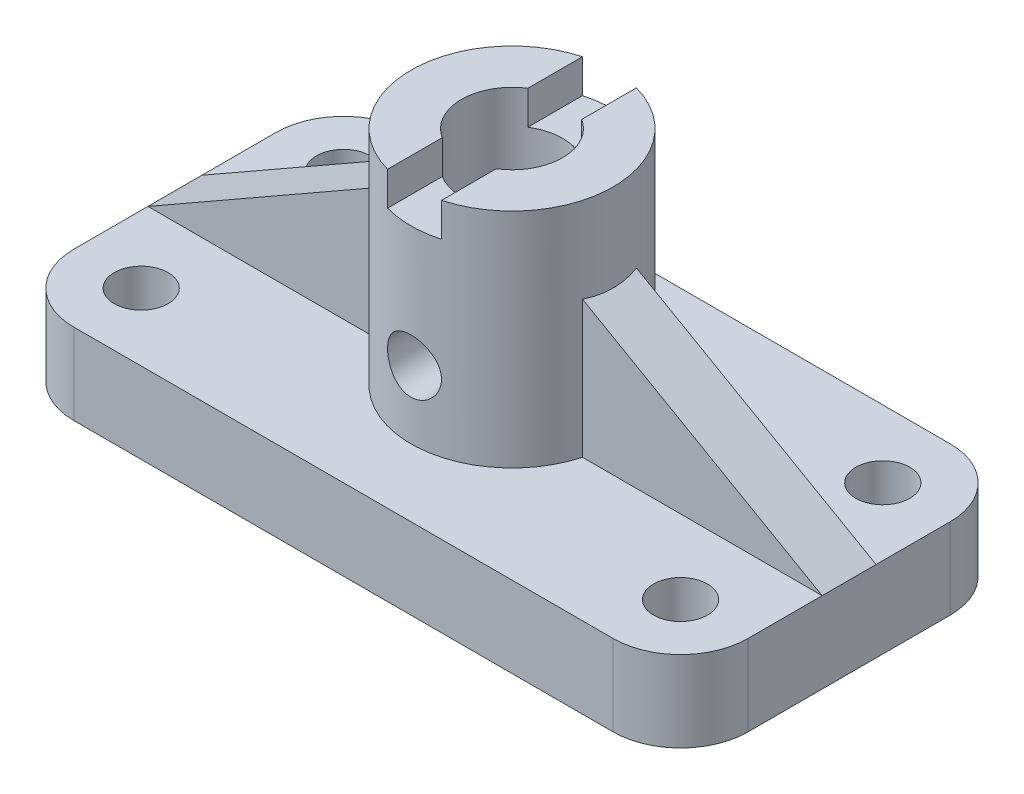
SolidWorks part; units mm, degrees
ref_plane "前视基准面" through (0, 0, 0) normal (0, 0, 1) x (1, 0, 0)
ref_plane "上视基准面" through (0, 0, 0) normal (0, 1, 0) x (1, 0, 0)
ref_plane "右视基准面" through (0, 0, 0) normal (1, 0, 0) x (0, 0, -1)
other "Configuration Table"
sketch "草图1" plane through (0, 0, 0) normal (0, 1, 0) x (1, 0, 0)
  line L1 (-40, -25) -> (40, -25)
  line L2 (-50, -15) -> (-50, 15)
  line L3 (-40, 25) -> (40, 25)
  line L4 (50, -15) -> (50, 15)
  line L5 (-50, -25) -> (50, 25) construction
  line L6 (-50, 25) -> (50, -25) construction
  line L7 (-40, -15) -> (40, -15) construction
  line L8 (-40, -15) -> (-40, 15) construction
  line L9 (-40, 15) -> (40, 15) construction
  line L10 (40, -15) -> (40, 15) construction
  line L11 (-40, -15) -> (40, 15) construction
  line L12 (-40, 15) -> (40, -15) construction
  arc A0 (-40, -25) -> (-50, -15) centre (-40, -15) cw
  arc A1 (40, -25) -> (50, -15) centre (40, -15) ccw
  arc A2 (40, 25) -> (50, 15) centre (40, 15) cw
  arc A3 (-50, 15) -> (-40, 25) centre (-40, 15) cw
  circle A4 centre (-40, 15) radius 4
  circle A5 centre (-40, -15) radius 4
  circle A6 centre (40, -15) radius 4
  circle A7 centre (40, 15) radius 4
  point P0 (0, 0)
  point P18 (0, 0)
  dimension "D3" = 10
  dimension "D6" = 8
  dimension "D7" = 8
  dimension "D8" = 8
  dimension "D9" = 8
  dimension "D1" = 50
  dimension "D2" = 100
  dimension "D4" = 80
  dimension "D5" = 30
extrude "凸台-拉伸1" add sketch "草图1" along normal blind 12
sketch "草图2" plane through (0, 12, 0) normal (0, 1, 0) x (1, 0, 0)
  circle A0 centre (0, 0) radius 15
  circle A1 centre (0, 0) radius 7.5
  dimension "D1" = 30
  dimension "D2" = 15
extrude "凸台-拉伸2" add sketch "草图2" along normal blind 33
sketch "草图3" plane through (0, 0, 25) normal (0, 0, 1) x (1, 0, 0)
  line L0 (0, 0) -> (0, 47.4371) construction
  line L1 (15, 45) -> (-15, 45) construction
  line L2 (-4, 40) -> (4, 40)
  line L3 (-4, 40) -> (-4, 45)
  line L4 (-4, 45) -> (4, 45)
  line L5 (4, 40) -> (4, 45)
  line L6 (-4, 40) -> (4, 45) construction
  line L7 (-4, 45) -> (4, 40) construction
  line L8 (-40, 12) -> (40, 12) construction
  circle A0 centre (0, 22) radius 4
  point P5 (0, 42.5)
  dimension "D4" = 8
  dimension "D1" = 8
  dimension "D2" = 5
  dimension "D3" = 10
extrude "切除-拉伸1" cut sketch "草图3" against normal through all
sketch "草图4" plane through (0, 0, 0) normal (0, 0, 1) x (1, 0, 0)
  line L0 (-50, 12) -> (-15, 32)
  line L1 (-15, 45) -> (-15, 12) construction
  line L2 (-40, 12) -> (40, 12) construction
  dimension "D1" = 20
rib "筋1" sketch "草图4" sketch "草图4" thickness 8 extrusion direction parallel to sketch draft on no parameters "D1"=8
mirror "镜向1" about plane through (0, 0, 0) normal (1, 0, 0) of "筋1"
